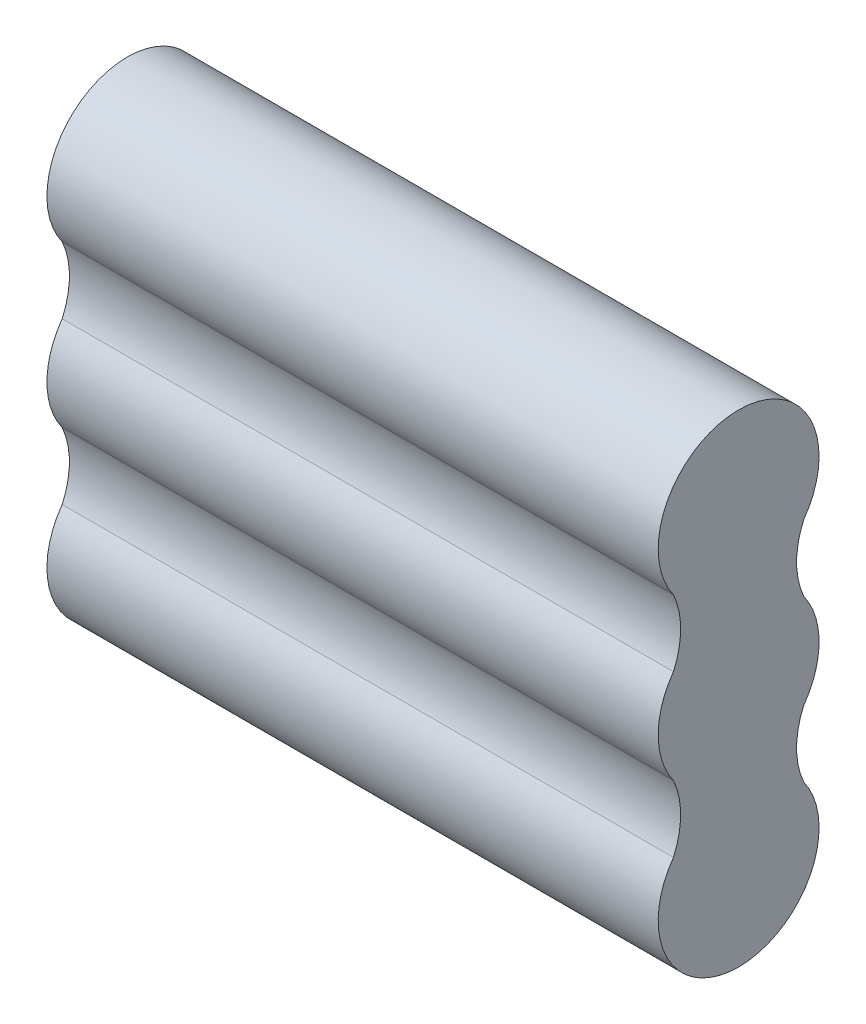
SolidWorks part; units mm, degrees
ref_plane "Front Plane" through (0, 0, 0) normal (0, 0, 1) x (1, 0, 0)
ref_plane "Top Plane" through (0, 0, 0) normal (0, 1, 0) x (1, 0, 0)
ref_plane "Right Plane" through (0, 0, 0) normal (1, 0, 0) x (0, 0, -1)
sketch "Sketch1" plane through (0, 0, 0) normal (0, 0, 1) x (1, 0, 0)
  line L1 (-33.782, 27.94) -> (33.782, 27.94)
  line L2 (-33.782, 27.94) -> (-33.782, -27.94)
  line L3 (-33.782, -27.94) -> (33.782, -27.94)
  line L4 (33.782, 27.94) -> (33.782, -27.94)
  line L5 (-33.782, 27.94) -> (33.782, -27.94) construction
  line L6 (-33.782, -27.94) -> (33.782, 27.94) construction
  point P0 (0, 0)
  dimension "D1" = 55.88
  dimension "D2" = 67.564
extrude "Boss-Extrude1" add sketch "Sketch1" along normal blind 17.78
sketch "Sketch2" plane through (33.782, 0, 0) normal (1, 0, 0) x (0, 0, -1)
  line L0 (0, -27.94) -> (0, 27.94) construction
  line L2 (-17.78, -27.94) -> (-17.78, 27.94) construction
  line L4 (-8.89, 17.78) -> (-8.89, 0) construction
  arc A0 (-1.6852, 12.572) -> (-16.0948, 12.572) centre (-8.89, 17.78) ccw
  arc A1 (-16.0948, 5.208) -> (-16.0948, -5.208) centre (-8.89, 0) ccw
  arc A2 (-16.0948, 12.572) -> (-16.0948, 5.208) centre (-24.1864, 8.89) cw
  arc A3 (-1.6852, 12.572) -> (-1.6852, 5.208) centre (6.4064, 8.89) ccw
  arc A4 (-16.0948, -12.572) -> (-16.0948, -5.208) centre (-24.1864, -8.89) ccw
  arc A5 (-1.6852, -12.572) -> (-16.0948, -12.572) centre (-8.89, -17.78) cw
  arc A6 (-1.6852, -12.572) -> (-1.6852, -5.208) centre (6.4064, -8.89) cw
  arc A7 (-1.6852, -5.208) -> (-1.6852, 5.208) centre (-8.89, 0) ccw
split "Split1" trim tools "Sketch2" bodies to split 101 resulting bodies 102
